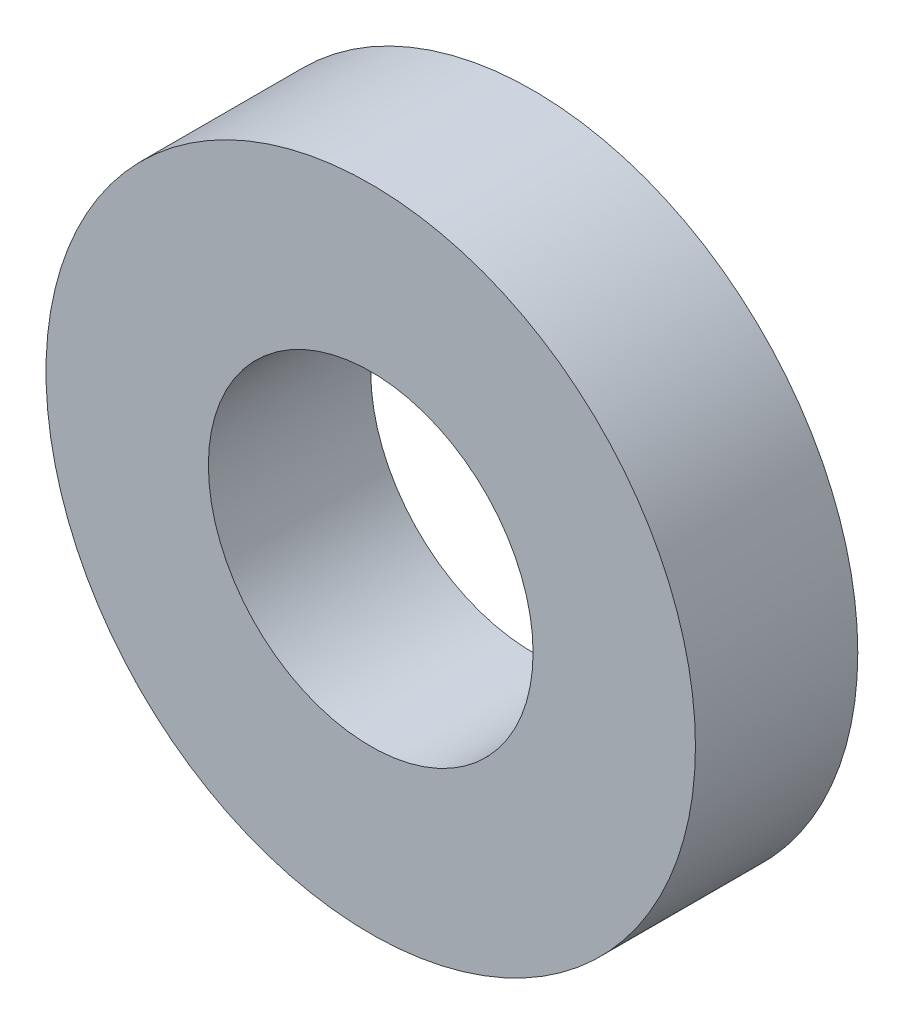
SolidWorks part; units mm, degrees
ref_plane "Front Plane" through (0, 0, 0) normal (0, 0, 1) x (1, 0, 0)
ref_plane "Top Plane" through (0, 0, 0) normal (0, 1, 0) x (1, 0, 0)
ref_plane "Right Plane" through (0, 0, 0) normal (1, 0, 0) x (0, 0, -1)
sketch "Sketch1" plane through (0, 0, 0) normal (0, 0, 1) x (1, 0, 0)
  circle A0 centre (0, 0) radius 3
  circle A1 centre (0, 0) radius 6
  dimension "D1" = 12
  dimension "D2" = 6
extrude "Boss-Extrude1" add sketch "Sketch1" along normal blind 3
